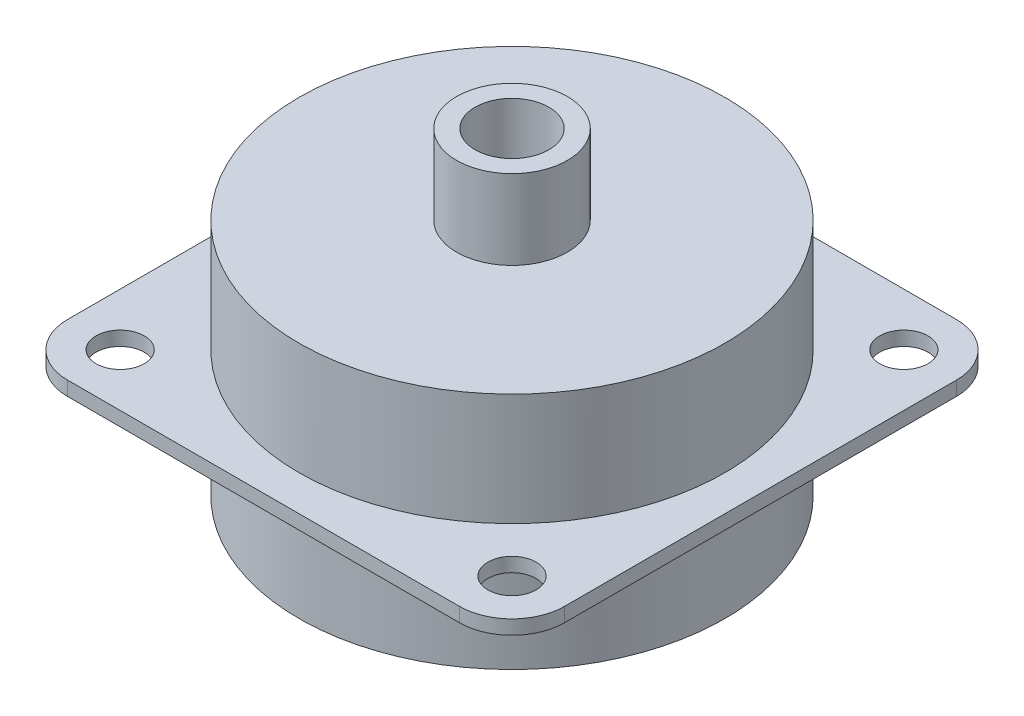
SolidWorks part; units mm, degrees
ref_plane "Front" through (0, 0, 0) normal (0, 0, 1) x (1, 0, 0)
ref_plane "Top" through (0, 0, 0) normal (0, 1, 0) x (1, 0, 0)
ref_plane "Right" through (0, 0, 0) normal (1, 0, 0) x (0, 0, -1)
sketch "Sketch1" plane through (0, 0, 0) normal (0, 0, 1) x (1, 0, 0)
  line L0 (-22.225, 0) -> (22.225, 0) construction
  line L1 (-22.225, 0) -> (-22.225, 1.27) construction
  line L2 (-22.225, 1.27) -> (-22.86, 1.27) construction
  line L3 (-22.86, 1.27) -> (-22.86, 18.034) construction
  line L4 (-3.302, 0) -> (-3.302, 35.814) construction
  line L5 (-3.302, 35.814) -> (3.302, 35.814) construction
  line L6 (3.302, 35.814) -> (3.302, 0) construction
  line L7 (3.302, 0) -> (-3.302, 0) construction
  line L8 (19.05, 18.034) -> (22.86, 18.034) construction
  line L9 (-19.05, 7.366) -> (-19.05, 28.702) construction
  line L10 (-19.05, 28.702) -> (-4.953, 28.702) construction
  line L12 (-4.953, 35.814) -> (4.953, 35.814) construction
  line L13 (4.953, 35.814) -> (4.953, 28.702) construction
  line L14 (4.953, 28.702) -> (19.05, 28.702) construction
  line L15 (19.05, 28.702) -> (19.05, 7.366) construction
  line L16 (19.05, 7.366) -> (3.302, 7.366) construction
  line L17 (22.86, 18.034) -> (22.86, 1.27) construction
  line L18 (22.86, 1.27) -> (22.225, 1.27) construction
  line L19 (22.225, 1.27) -> (22.225, 0) construction
  line L20 (-4.953, 35.814) -> (-4.953, 28.702) construction
  line L22 (0, 35.814) -> (0, 7.366) construction
  line L23 (-17.526, 0) -> (17.526, 0) construction
  line L24 (-22.86, 18.034) -> (-19.05, 18.034) construction
  line L25 (-19.05, 7.366) -> (-3.302, 7.366) construction
  point P10 (0, 35.814)
  point P26 (0, 0)
  dimension "D1" = 9.906
  dimension "D3" = 45.72
  dimension "D2" = 7.112
sketch "Sketch2" plane through (0, 0, 0) normal (0, 0, 1) x (1, 0, 0)
  line L0 (3.302, 35.814) -> (4.953, 35.814)
  line L1 (4.953, 35.814) -> (4.953, 28.702)
  line L2 (4.953, 28.702) -> (19.05, 28.702)
  line L3 (19.05, 28.702) -> (19.05, 18.669)
  line L4 (19.05, 28.702) -> (19.05, 7.366) construction
  line L5 (19.05, 18.669) -> (22.86, 18.669) construction
  line L6 (22.86, 17.399) -> (22.86, 18.669) construction
  line L7 (22.86, 18.034) -> (22.86, 1.27) construction
  line L9 (22.86, 17.399) -> (19.05, 17.399) construction
  line L10 (19.05, 17.399) -> (19.05, 7.366)
  line L11 (19.05, 7.366) -> (3.302, 7.366)
  line L12 (3.302, 35.814) -> (3.302, 0) construction
  line L13 (3.302, 7.366) -> (3.302, 35.814)
  line L14 (19.05, 17.399) -> (19.05, 18.669)
  line L17 (22.225, 1.27) -> (22.225, 0) construction
revolve "Revolve1" add sketch "Sketch2" angle 360 mid plane about L22
ref_plane "Plane1" through (0, 17.399, 0) normal (0, 1, 0) x (-1, 0, 0)
sketch "Sketch3" plane through (0, 17.399, 0) normal (0, 1, 0) x (1, 0, 0)
  line L1 (-17.526, 22.225) -> (17.526, 22.225)
  line L2 (-22.225, 17.526) -> (-22.225, -17.526)
  line L3 (-17.526, -22.225) -> (17.526, -22.225)
  line L4 (22.225, 17.526) -> (22.225, -17.526)
  line L5 (-22.225, 22.225) -> (22.225, -22.225) construction
  line L6 (-22.225, -22.225) -> (22.225, 22.225) construction
  circle A1 centre (0, 0) radius 19.05
  circle A2 centre (-17.526, -17.526) radius 2.159
  circle A3 centre (17.526, -17.526) radius 2.159
  circle A4 centre (-17.526, 17.526) radius 2.159
  circle A5 centre (17.526, 17.526) radius 2.159
  arc A6 (17.526, -22.225) -> (22.225, -17.526) centre (17.526, -17.526) ccw
  arc A7 (17.526, 22.225) -> (22.225, 17.526) centre (17.526, 17.526) cw
  arc A8 (-17.526, 22.225) -> (-22.225, 17.526) centre (-17.526, 17.526) ccw
  arc A9 (-22.225, -17.526) -> (-17.526, -22.225) centre (-17.526, -17.526) ccw
  circle A10 centre (0, 0) radius 19.05 construction
  point P0 (0, 0)
  dimension "Mounting Hole Dia" = 4.318
extrude "Boss-Extrude1" add sketch "Sketch3" along normal up to vertex (1.27 mm away) up to point (22.86, 18.669, 0)
equation "\"D1@Sketch1\" = \"Center Hole Dia@Sketch1\" * 1.5"
equation "\"D3@Sketch1\" = \"Body Dia (C)@Sketch1\" * 1.2"
equation "\"D2@Sketch1\" = \"Body Ht@Sketch1\" * .25"
